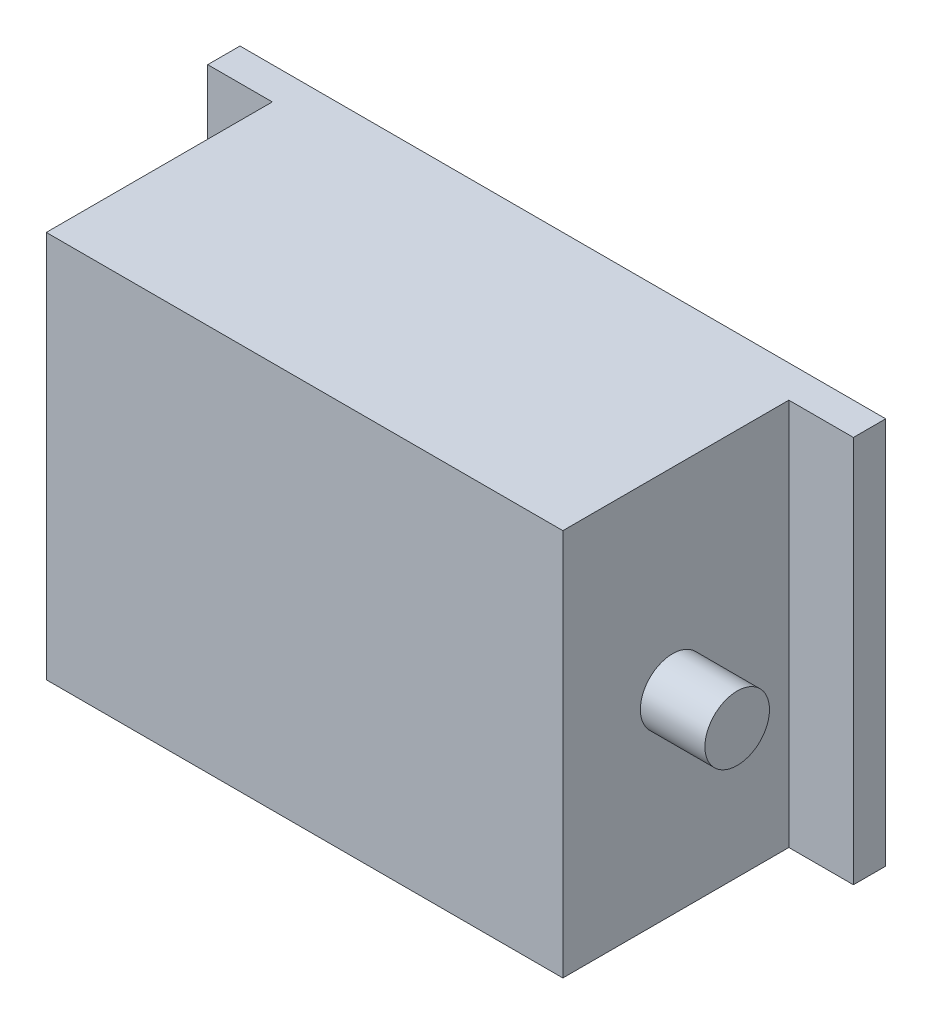
SolidWorks part; units mm, degrees
ref_plane "Front Plane" through (0, 0, 0) normal (0, 0, 1) x (1, 0, 0)
ref_plane "Top Plane" through (0, 0, 0) normal (0, 1, 0) x (1, 0, 0)
ref_plane "Right Plane" through (0, 0, 0) normal (1, 0, 0) x (0, 0, -1)
sketch "Sketch1" plane through (0, 0, 0) normal (0, 0, 1) x (1, 0, 0)
  line L1 (0, 0) -> (100, 0)
  line L2 (0, 0) -> (0, 60)
  line L3 (0, 60) -> (100, 60)
  line L4 (100, 0) -> (100, 60)
  dimension "D1" = 100
  dimension "D2" = 60
extrude "Boss-Extrude1" add sketch "Sketch1" along normal blind 40
sketch "Sketch2" plane through (0, 0, 0) normal (0, -1, 0) x (1, 0, 0)
  line L0 (0, 0) -> (100, 0) construction
  line L1 (0, 40) -> (10, 40)
  line L2 (0, 40) -> (0, 5)
  line L3 (0, 5) -> (10, 5)
  line L4 (10, 40) -> (10, 5)
  line L5 (100, 40) -> (90, 40)
  line L6 (100, 40) -> (100, 5)
  line L7 (100, 5) -> (90, 5)
  line L8 (90, 40) -> (90, 5)
  dimension "D1" = 5
  dimension "D2" = 10
  dimension "D3" = 10
extrude "Cut-Extrude1" cut sketch "Sketch2" against normal through all
sketch "Sketch3" plane through (10, 0, 0) normal (-1, 0, 0) x (0, 0, 1)
  line L0 (5, 0) -> (40, 0) construction
  line L1 (40, 60) -> (40, 0) construction
  circle A0 centre (20, 30) radius 10
  dimension "D3" = 20
  dimension "D1" = 30
  dimension "D2" = 20
extrude "Cut-Extrude2" cut sketch "Sketch3" against normal blind 10
sketch "Sketch4" plane through (90, 0, 0) normal (1, 0, 0) x (0, 0, -1)
  line L0 (-40, 60) -> (-40, 0) construction
  line L1 (-40, 60) -> (-5, 60) construction
  circle A0 centre (-23, 30) radius 5
  dimension "D3" = 10
  dimension "D1" = 17
  dimension "D2" = 30
extrude "Boss-Extrude2" add sketch "Sketch4" along normal blind 10
